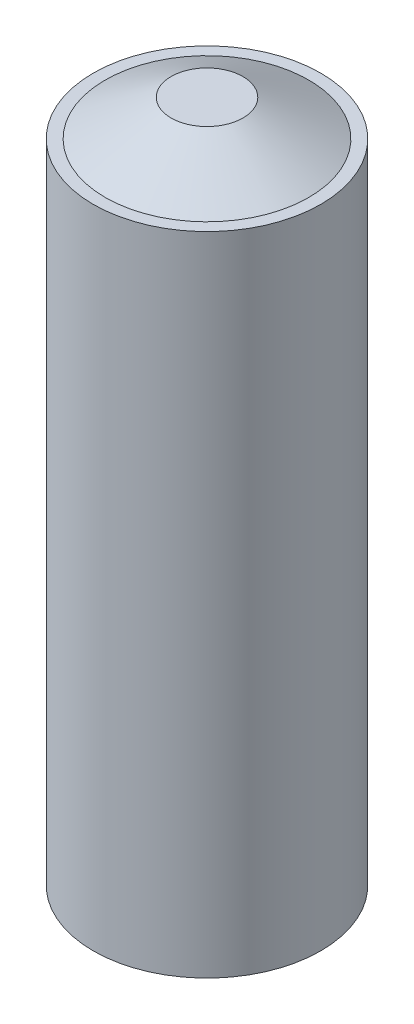
SolidWorks part; units mm, degrees
ref_plane "Front Plane" through (0, 0, 0) normal (0, 0, 1) x (1, 0, 0)
ref_plane "Top Plane" through (0, 0, 0) normal (0, 1, 0) x (1, 0, 0)
ref_plane "Right Plane" through (0, 0, 0) normal (1, 0, 0) x (0, 0, -1)
sketch "Sketch1" plane through (0, 0, 0) normal (0, 0, 1) x (1, 0, 0)
  line L0 (0, 60) -> (0, -60) construction
  line L1 (19, 54) -> (19, -54)
  line L2 (0, 60) -> (6, 60)
  line L3 (19, 54) -> (17, 54)
  line L4 (0, -60) -> (6, -60)
  line L5 (17, 54) -> (6, 60)
  line L6 (19, -54) -> (17, -54)
  line L7 (17, -54) -> (6, -60)
  line L8 (0, 60) -> (0, -60)
  dimension "D1" = 120
  dimension "D2" = 38
  dimension "D3" = 12
  dimension "D4" = 2
  dimension "D5" = 6
revolve "Revolve1" add sketch "Sketch1" angle 360 about L8
